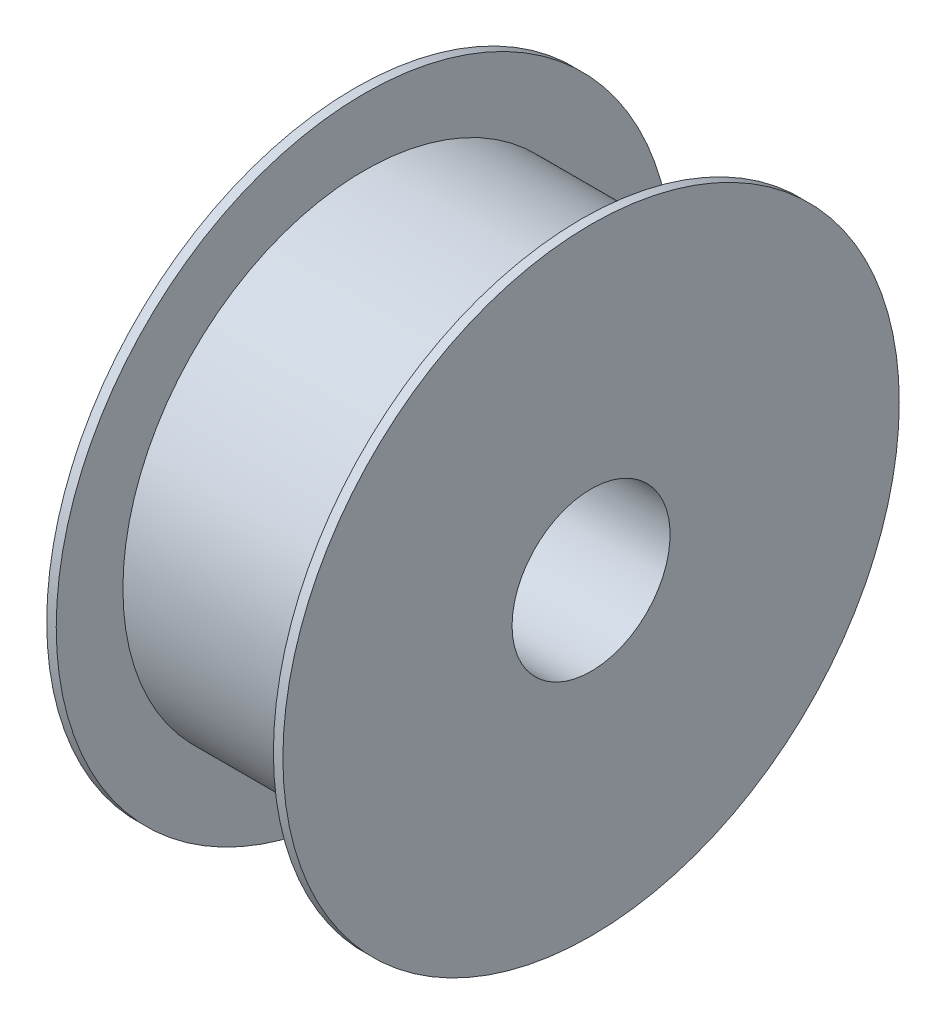
SolidWorks part; units mm, degrees
ref_plane "Front Plane" through (0, 0, 0) normal (0, 0, 1) x (1, 0, 0)
ref_plane "Top Plane" through (0, 0, 0) normal (0, 1, 0) x (1, 0, 0)
ref_plane "Right Plane" through (0, 0, 0) normal (1, 0, 0) x (0, 0, -1)
sketch "Sketch1" plane through (0, 0, 0) normal (0, 1, 0) x (1, 0, 0)
  line L0 (0, 58.783) -> (0, 131.283)
  line L1 (0, 131.283) -> (3, 131.283)
  line L2 (3, 131.283) -> (3, 110.1891)
  line L3 (3, 110.1891) -> (71.7075, 110.1891)
  line L4 (71.7075, 110.1891) -> (71.7075, 131.283)
  line L5 (71.7075, 131.283) -> (74.7075, 131.283)
  line L6 (74.7075, 131.283) -> (74.7075, 58.783)
  line L7 (74.7075, 58.783) -> (0, 58.783)
  line L8 (-2.3274, 33.783) -> (77, 33.783) construction
  dimension "D1" = 97.5
  dimension "D2" = 25
  dimension "D3" = 3
  dimension "D4" = 3
revolve "Revolve1" add sketch "Sketch1" angle 360 about L8
